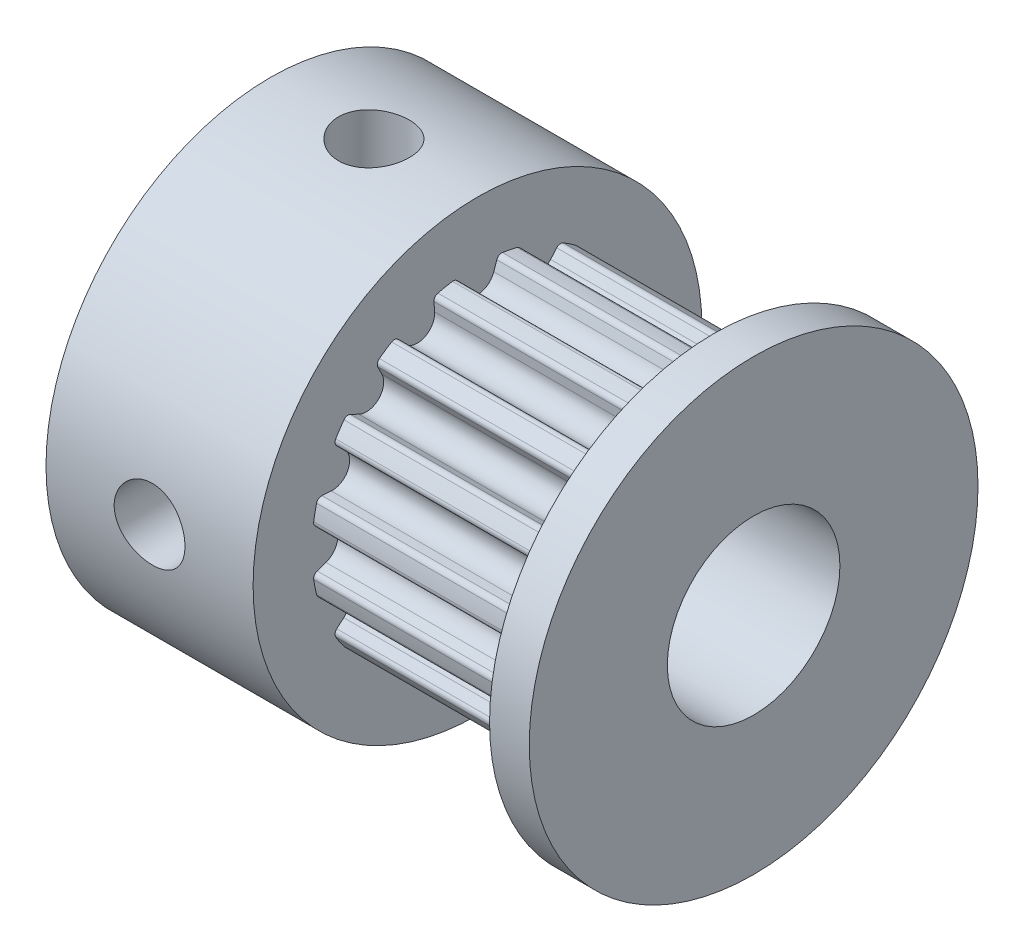
SolidWorks part; units mm, degrees
ref_plane "Alzado" through (0, 0, 0) normal (0, 0, 1) x (1, 0, 0)
ref_plane "Planta" through (0, 0, 0) normal (0, 1, 0) x (1, 0, 0)
ref_plane "Vista lateral" through (0, 0, 0) normal (1, 0, 0) x (0, 0, -1)
sketch "Croquis1" plane through (0, 0, 0) normal (1, 0, 0) x (0, 0, -1)
  circle A0 centre (0, 0) radius 6.5
  dimension "D1" = 13
extrude "Corpo Lado Motor - Ø13x6" add sketch "Croquis1" along normal blind 6
sketch "Croquis3" plane through (6, 0, 0) normal (1, 0, 0) x (0, 0, -1)
  circle A0 centre (0, 0) radius 4.8
  dimension "D1" = 9.6
extrude "Corpo dos Dentes Ø9.6x6.85" add sketch "Croquis3" along normal blind 6.85
sketch "Croquis5" plane through (6, 0, 0) normal (1, 0, 0) x (0, 0, -1)
  line L0 (0, 4.8) -> (0, 4.55) construction
  line L1 (-0.4735, 4.3894) -> (-0.6, 4.7624)
  line L2 (0.4735, 4.3894) -> (0.6, 4.7624)
  arc A1 (-0.4735, 4.3894) -> (0.4735, 4.3894) centre (0, 4.55) ccw
  arc A2 (0.6, 4.7624) -> (-0.6, 4.7624) centre (0, 0) ccw
  arc A3 (-0.6, 4.7624) -> (0.6, 4.7624) centre (0, 0) ccw construction
  dimension "D3" = 9.6
  dimension "D1" = 0.5
  dimension "D2" = 0.75
  dimension "D4" = 1.2
extrude "Corte do Dente - R0.5" cut sketch "Croquis5" along normal up to next
fillet "Arredondamento - Raio 0.15mm" radius 0.15 2 edges at (9.425, 4.7624, -0.6) (9.425, 4.7624, 0.6)
pattern_circular "Corte dos 16 Dentes" count 16 over 360 about axis through (0, 0, 0) along (1, 0, 0) of "Corte do Dente - R0.5", "Arredondamento - Raio 0.15mm"
sketch "Croquis4" plane through (12.85, 0, 0) normal (1, 0, 0) x (0, 0, -1)
  circle A0 centre (0, 0) radius 6.5
  dimension "D1" = 13
extrude "Face Direita Ø20" add sketch "Croquis4" along normal blind 1.15
sketch "Croquis6" plane through (0, 0, 0) normal (-1, 0, 0) x (0, 0, 1)
  circle A0 centre (0, 0) radius 2.5
  dimension "D1" = 5
extrude "Furo Passante Ø5" cut sketch "Croquis6" against normal up to surface (14 mm away) up to face at (14, 0, -6.5)
ref_plane "Plano de Referência" through (0, 6.5, 0) normal (0, 1, 0) x (1, 0, 0)
hole_wizard "Furo de Fixação 1 - M2.5" positions "Sketch4" profile "Sketch5" tap size "M2.5x0.45" standard "ANSI Metric"
sketch "Sketch4" plane through (0, 6.5, 0) normal (0, 1, 0) x (1, 0, 0)
  line L0 (0, 0) -> (6, 0) construction
  line L3 (6, -6.5) -> (6, 6.5) construction
  point P0 (3, 0)
  point P11 (3, 0)
sketch "Sketch5" plane through (3, 6.5, 0) normal (1, 0, 0) x (0, 0, 1)
  line L0 (0, 0) -> (0, 4)
  line L1 (0, 4) -> (1.025, 4)
  line L2 (1.025, 4) -> (1.025, 0)
  line L5 (1.025, 0) -> (0, 0)
  line L11 (0, -6.35) -> (0, 107.95) construction
  dimension "Thru Tap Drill Dia." = 2.05
  dimension "Thru Tap Drill Depth" = 4
cosmetic thread "Hole Thread2" parameters "D2"=2.5
pattern_circular "Furo de Fixação 2 - M2.5" count 2 every 90 about axis through (21.0711, 0, 0) along (-1, 0, 0) of "Furo de Fixação 1 - M2.5"
